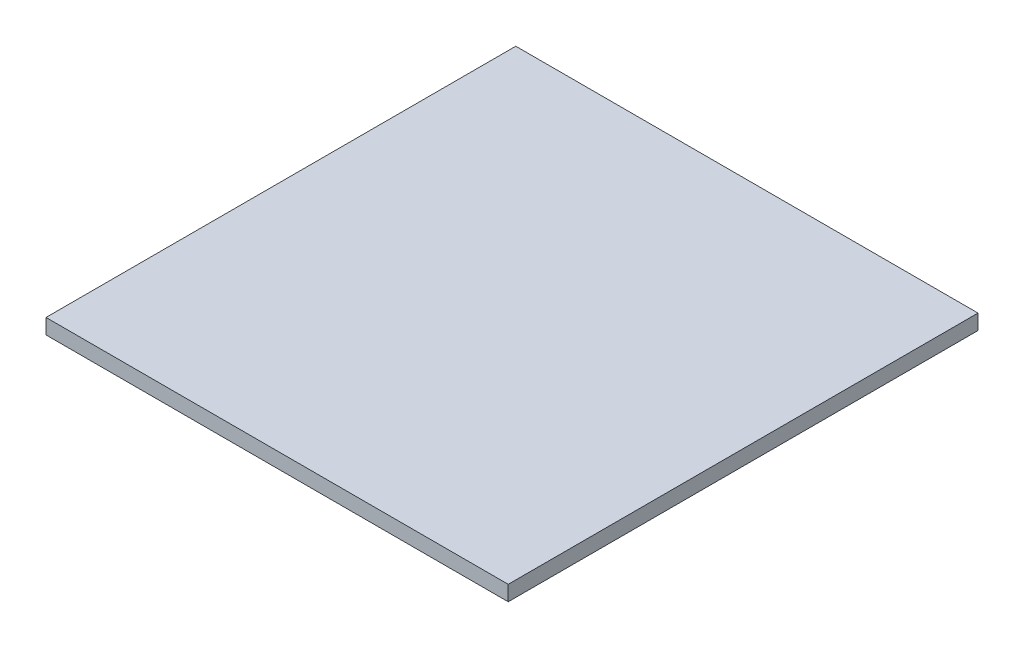
SolidWorks part; units mm, degrees
ref_plane "Front Plane" through (0, 0, 0) normal (0, 0, 1) x (1, 0, 0)
ref_plane "Top Plane" through (0, 0, 0) normal (0, 1, 0) x (1, 0, 0)
ref_plane "Right Plane" through (0, 0, 0) normal (1, 0, 0) x (0, 0, -1)
sketch "Sketch1" plane through (0, 0, 0) normal (0, 1, 0) x (1, 0, 0)
  line L1 (-152.5, -155) -> (152.5, -155)
  line L2 (-152.5, -155) -> (-152.5, 155)
  line L3 (-152.5, 155) -> (152.5, 155)
  line L4 (152.5, -155) -> (152.5, 155)
  line L5 (-152.5, -155) -> (152.5, 155) construction
  line L6 (-152.5, 155) -> (152.5, -155) construction
  point P0 (0, 0)
  dimension "D1" = 310
  dimension "D2" = 305
extrude "Boss-Extrude1" add sketch "Sketch1" along normal blind 10
